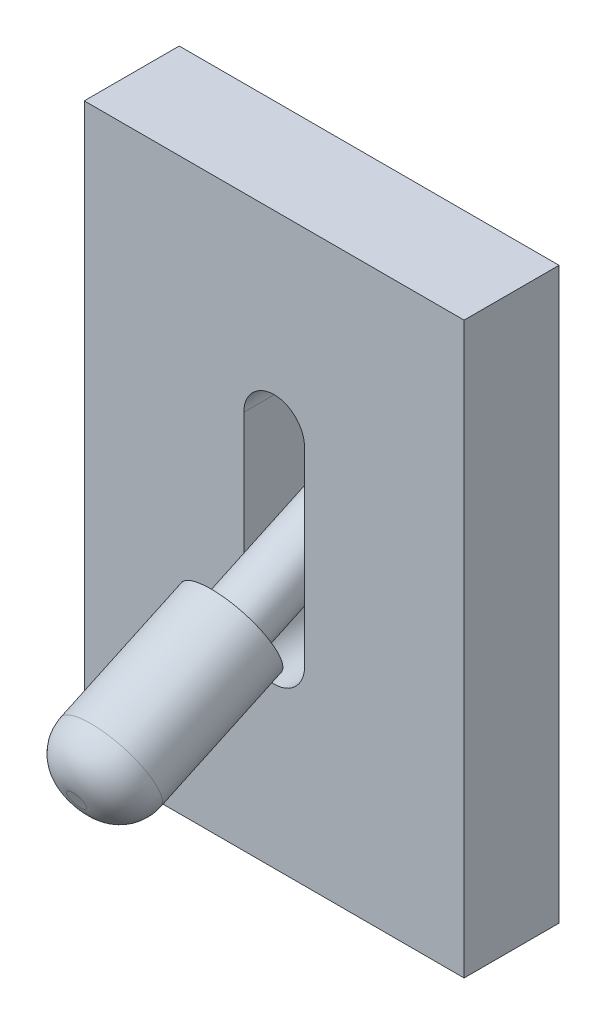
SolidWorks part; units mm, degrees
ref_plane "Спереди" through (0, 0, 0) normal (0, 0, 1) x (1, 0, 0)
ref_plane "Сверху" through (0, 0, 0) normal (0, 1, 0) x (1, 0, 0)
ref_plane "Справа" through (0, 0, 0) normal (1, 0, 0) x (0, 0, -1)
ref_plane "Плоскость4" through (0, 0, -2) normal (0, 0, -1) x (-1, 0, 0)
sketch "Эскиз1" plane through (0, 0, -2) normal (0, 0, -1) x (-1, 0, 0)
  line L1 (146, -25) -> (126, -25)
  line L2 (146, -25) -> (146, 5)
  line L3 (146, 5) -> (126, 5)
  line L4 (126, -25) -> (126, 5)
  line L5 (146, -25) -> (126, 5) construction
  line L6 (146, 5) -> (126, -25) construction
  point P0 (136, -10)
  dimension "D1" = 20
  dimension "D2" = 30
extrude "Бобышка-Вытянуть1" add sketch "Эскиз1" along normal up to surface (5 mm away)
sketch "Эскиз2" plane through (0, 0, -2) normal (0, 0, 1) x (1, 0, 0)
  line L0 (-136, -5) -> (-136, -15) construction
  line L1 (-134.4, -5) -> (-134.4, -15)
  line L2 (-137.6, -5) -> (-137.6, -15)
  arc A0 (-134.4, -5) -> (-137.6, -5) centre (-136, -5) ccw
  arc A1 (-137.6, -15) -> (-134.4, -15) centre (-136, -15) ccw
  point P4 (-136, -10)
  dimension "D1" = 1.6
extrude "Вырез-Вытянуть1" cut sketch "Эскиз2" against normal up to next
ref_plane "Плоскость5" through (-136, 0, 0) normal (1, 0, 0) x (0, 0, -1)
ref_plane "Плоскость6" through (-136, 0, 0) normal (1, 0, 0) x (0, 0, -1)
sketch "Эскиз4" plane through (-136, 0, -136) normal (1, 0, 0) x (0, 0, -1)
  line L0 (-141.7986, -9.5) -> (-117.713, -9.5) construction
  line L1 (-129, -9.5) -> (-167.227, -27.3255) construction
  line L3 (-144.4072, -16.6845) -> (-145.4638, -14.4187)
  line L4 (-145.4638, -14.4187) -> (-137.307, -10.6152)
  line L5 (-137.307, -10.6152) -> (-136.8844, -11.5215)
  line L6 (-136.8844, -11.5215) -> (-129.6339, -8.1405)
  line L7 (-129.6339, -8.1405) -> (-129, -9.5)
  line L8 (-129, -9.5) -> (-144.4072, -16.6845)
  line L9 (-129, -25) -> (-129, 5) construction
  dimension "D1" = 25
  dimension "D2" = 8
  dimension "D3" = 9
  dimension "D4" = 2.5
  dimension "D5" = 1.5
revolve "Повернуть1" add sketch "Эскиз4" angle 360 about L1
fillet "Скругление1" radius 2 1 edges at (-136, -14.4187, 9.4638)
